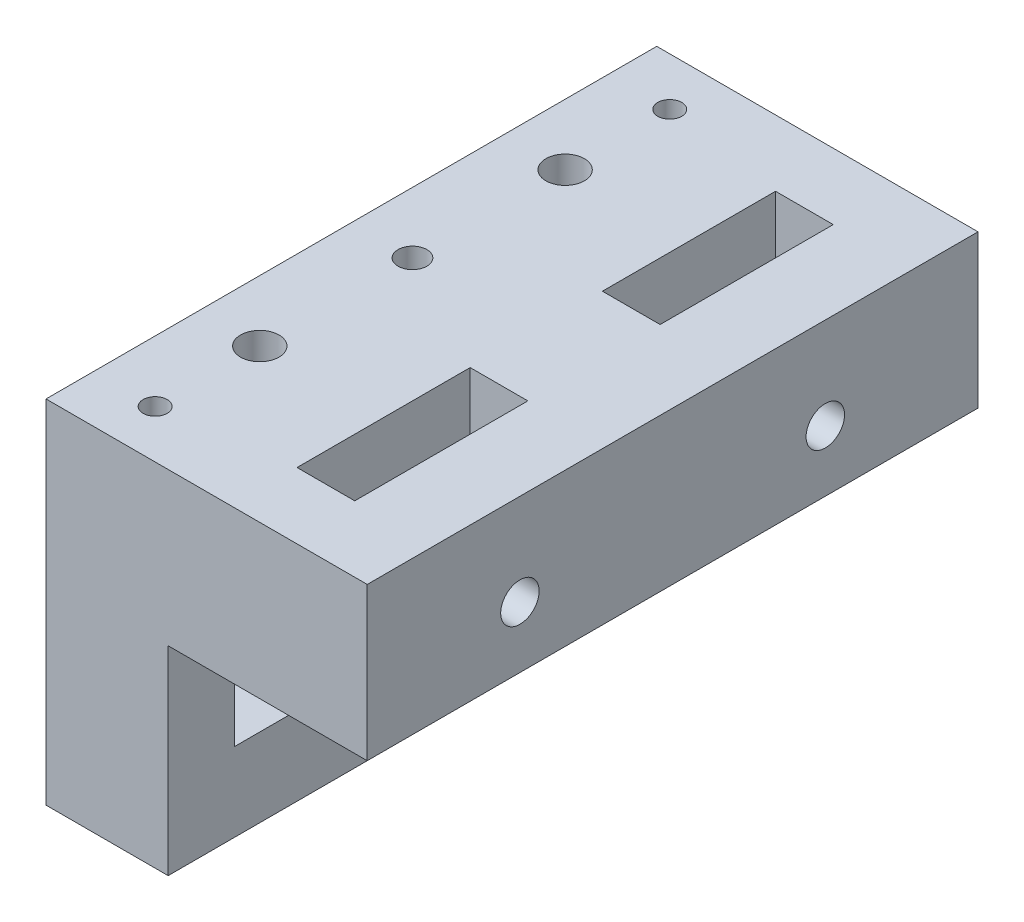
SolidWorks part; units mm, degrees
ref_plane "Front Plane" through (0, 0, 0) normal (0, 0, 1) x (1, 0, 0)
ref_plane "Top Plane" through (0, 0, 0) normal (0, 1, 0) x (1, 0, 0)
ref_plane "Right Plane" through (0, 0, 0) normal (1, 0, 0) x (0, 0, -1)
sketch "Sketch1" plane through (0, 0, 0) normal (0, 1, 0) x (1, 0, 0)
  line L1 (-22.225, -31.75) -> (22.225, -31.75)
  line L2 (-22.225, -31.75) -> (-22.225, 31.75)
  line L3 (-22.225, 31.75) -> (22.225, 31.75)
  line L4 (22.225, -31.75) -> (22.225, 31.75)
  line L5 (-22.225, -31.75) -> (22.225, 31.75) construction
  line L6 (-22.225, 31.75) -> (22.225, -31.75) construction
  line L7 (0, 31.75) -> (0, 0)
  line L8 (0, 0) -> (0, -31.75)
  line L9 (-3, 24.875) -> (3, 24.875)
  line L10 (-3, 24.875) -> (-3, 6.875)
  line L11 (-3, 6.875) -> (3, 6.875)
  line L12 (3, 24.875) -> (3, 6.875)
  line L13 (-3, 24.875) -> (3, 6.875) construction
  line L14 (-3, 6.875) -> (3, 24.875) construction
  line L15 (-3, -6.875) -> (3, -6.875)
  line L16 (-3, -6.875) -> (-3, -24.875)
  line L17 (-3, -24.875) -> (3, -24.875)
  line L18 (3, -6.875) -> (3, -24.875)
  line L19 (-3, -6.875) -> (3, -24.875) construction
  line L20 (-3, -24.875) -> (3, -6.875) construction
  point P0 (0, 0)
  point P8 (0, 15.875)
  point P14 (0, -15.875)
  dimension "D1" = 44.45
  dimension "D2" = 63.5
  dimension "D3" = 18
  dimension "D4" = 18
  dimension "D5" = 6
  dimension "D6" = 6
extrude "Boss-Extrude1" add sketch "Sketch1" along normal blind 12.7 contours L17 L16 L15 L8 L7 L11 L10 L9 L3 L2 L1 | L15 L18 L17 L8 L1 L4 L3 L7 L9 L12 L11
sketch "Sketch2" plane through (0, 0, 0) normal (0, -1, 0) x (1, 0, 0)
  line L0 (-22.225, -31.75) -> (22.225, -31.75) construction
  line L1 (-22.225, 31.75) -> (-9.525, 31.75)
  line L2 (-22.225, 31.75) -> (-22.225, -31.75)
  line L3 (-22.225, -31.75) -> (-9.525, -31.75)
  line L4 (-9.525, 31.75) -> (-9.525, -31.75)
  dimension "D1" = 12.7
extrude "Boss-Extrude2" add sketch "Sketch2" along normal blind 31.75
sketch "Sketch3" plane through (-22.225, 0, 0) normal (-1, 0, 0) x (0, 0, 1)
  line L0 (-31.75, -9.525) -> (0, -9.525)
  line L1 (-31.75, 12.7) -> (-31.75, -31.75) construction
  line L2 (0, -9.525) -> (31.75, -9.525)
  line L3 (31.75, 12.7) -> (31.75, -31.75) construction
  line L5 (-24.875, -6.525) -> (-6.875, -6.525)
  line L6 (-24.875, -6.525) -> (-24.875, -12.525)
  line L7 (-24.875, -12.525) -> (-6.875, -12.525)
  line L8 (-6.875, -6.525) -> (-6.875, -12.525)
  line L9 (-24.875, -6.525) -> (-6.875, -12.525) construction
  line L10 (-24.875, -12.525) -> (-6.875, -6.525) construction
  line L11 (6.875, -6.525) -> (24.875, -6.525)
  line L12 (6.875, -6.525) -> (6.875, -12.525)
  line L13 (6.875, -12.525) -> (24.875, -12.525)
  line L14 (24.875, -6.525) -> (24.875, -12.525)
  line L15 (6.875, -6.525) -> (24.875, -12.525) construction
  line L16 (6.875, -12.525) -> (24.875, -6.525) construction
  point P4 (-15.875, -9.525)
  point P12 (15.875, -9.525)
  dimension "D1" = 6
  dimension "D2" = 6
  dimension "D3" = 18
  dimension "D5" = 18
extrude "Cut-Extrude1" cut sketch "Sketch3" against normal blind 19.05 contours L8 L5 L6 L0 | L8 L0 L6 L7 | L14 L11 L12 L2 | L14 L2 L12 L13
sketch "Sketch4" plane through (0, 12.7, 0) normal (0, 1, 0) x (1, 0, 0)
  line L0 (-22.225, 31.75) -> (-15.875, 31.75)
  line L1 (-22.225, 31.75) -> (22.225, 31.75) construction
  line L2 (-15.875, 31.75) -> (-15.875, 15.875)
  line L3 (-15.875, 15.875) -> (-15.875, -15.875)
  circle A0 centre (-15.875, 15.875) radius 2
  circle A1 centre (-15.875, -15.875) radius 2
  dimension "D1" = 6.35
  dimension "D2" = 15.875
  dimension "D3" = 31.75
extrude "Cut-Extrude2" cut sketch "Sketch4" against normal through all
sketch "Sketch5" plane through (-22.225, 0, 0) normal (-1, 0, 0) x (0, 0, 1)
  line L0 (-31.75, 12.7) -> (-31.75, 6.35)
  line L1 (-31.75, 12.7) -> (-31.75, -31.75) construction
  line L2 (-31.75, 6.35) -> (-15.875, 6.35)
  line L3 (-15.875, 6.35) -> (15.875, 6.35)
  circle A0 centre (-15.875, 6.35) radius 2
  circle A1 centre (15.875, 6.35) radius 2
  dimension "D1" = 6.35
  dimension "D2" = 31.75
  dimension "D3" = 15.875
extrude "Cut-Extrude3" cut sketch "Sketch5" against normal through all
sketch "Sketch6" plane through (22.225, 0, 0) normal (1, 0, 0) x (0, 0, -1)
  line L1 (-31.75, 12.7) -> (31.75, 12.7)
  line L2 (-31.75, 12.7) -> (-31.75, 0)
  line L3 (-31.75, 0) -> (31.75, 0)
  line L4 (31.75, 12.7) -> (31.75, 0)
extrude "Cut-Extrude4" cut sketch "Sketch6" against normal blind 11.05
sketch "Sketch7" plane through (0, -31.75, 0) normal (0, -1, 0) x (1, 0, 0)
  line L1 (-22.225, 31.75) -> (-9.525, 31.75)
  line L2 (-22.225, 31.75) -> (-22.225, -31.75)
  line L3 (-22.225, -31.75) -> (-9.525, -31.75)
  line L4 (-9.525, 31.75) -> (-9.525, -31.75)
extrude "Cut-Extrude5" cut sketch "Sketch7" against normal blind 11.05
sketch "Sketch8" plane through (0, 12.7, 0) normal (0, 1, 0) x (1, 0, 0)
  line L1 (-22.225, 31.75) -> (11.175, 31.75)
  line L2 (-22.225, 31.75) -> (-22.225, -31.75)
  line L3 (-22.225, -31.75) -> (11.175, -31.75)
  line L4 (11.175, 31.75) -> (11.175, -31.75)
  line L5 (3, -24.875) -> (-3, -24.875)
  line L6 (3, -24.875) -> (3, -6.875)
  line L7 (3, -6.875) -> (-3, -6.875)
  line L8 (-3, -24.875) -> (-3, -6.875)
  line L9 (-3, 6.875) -> (3, 6.875)
  line L10 (-3, 6.875) -> (-3, 24.875)
  line L11 (-3, 24.875) -> (3, 24.875)
  line L12 (3, 6.875) -> (3, 24.875)
  circle A0 centre (-15.875, 15.875) radius 2
  circle A1 centre (-15.875, -15.875) radius 2
extrude "Boss-Extrude3" add sketch "Sketch8" along normal blind 3.175
sketch "Sketch9" plane through (0, 15.875, 0) normal (0, 1, 0) x (1, 0, 0)
  line L0 (-15.875, 31.75) -> (-22.225, 31.75)
  line L1 (-15.875, 13.875) -> (-15.875, -13.875)
  line L2 (-22.225, 31.75) -> (-15.875, 31.75)
  line L3 (-15.875, 31.75) -> (-15.875, 26.75)
  line L4 (-22.225, -31.75) -> (-15.875, -31.75)
  line L5 (-22.225, -31.75) -> (11.175, -31.75) construction
  line L6 (-15.875, -31.75) -> (-15.875, -26.75)
  line L7 (-15.875, -26.75) -> (6.35, -26.75)
  line L8 (-15.875, 26.75) -> (6.35, 26.75)
  circle A0 centre (-15.875, 26.75) radius 1.25
  circle A1 centre (-15.875, -26.75) radius 1.25
  circle A2 centre (6.35, 26.75) radius 1.25
  circle A3 centre (6.35, -26.75) radius 1.25
  circle A7 centre (-15.875, 15.875) radius 2 construction
  circle A8 centre (-15.875, -15.875) radius 2 construction
  circle A9 centre (-15.875, 0) radius 1.5
  dimension "D3" = 5
  dimension "D4" = 22.225
  dimension "D1" = 5
  dimension "D2" = 6.35
  dimension "D5" = 22.225
extrude "Cut-Extrude6" cut sketch "Sketch9" against normal through all contours A0 | A1 | A9
